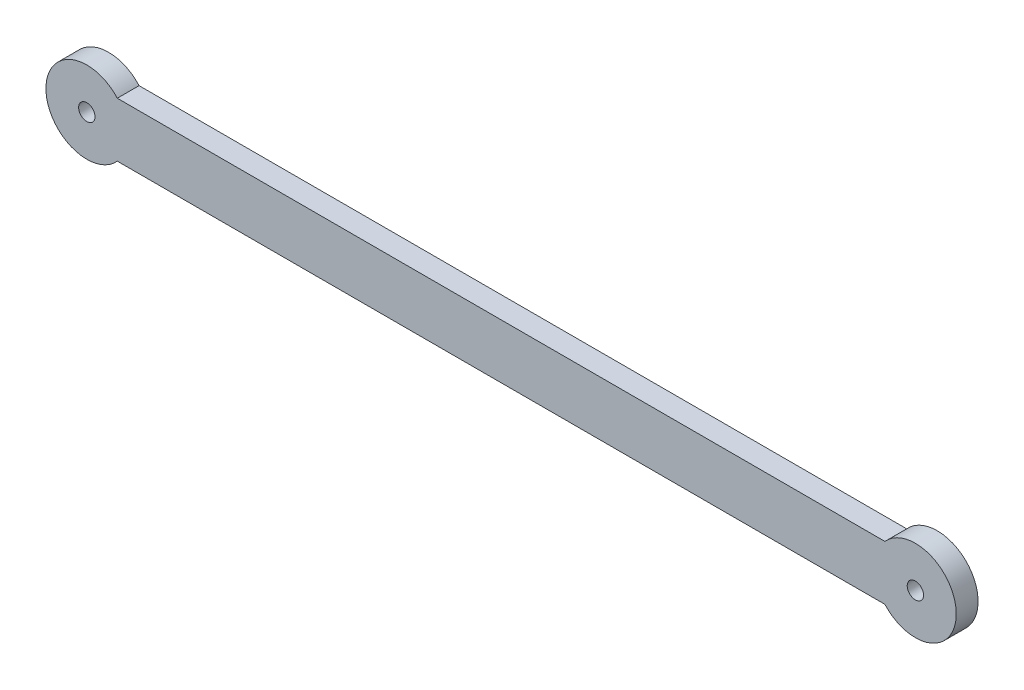
SolidWorks part; units mm, degrees
material "Acrílico (Impacto medio-alto)"
ref_plane "Piano frontale" through (0, 0, 0) normal (0, 0, 1) x (1, 0, 0)
ref_plane "Piano superiore" through (0, 0, 0) normal (0, 1, 0) x (1, 0, 0)
ref_plane "Piano destro" through (0, 0, 0) normal (1, 0, 0) x (0, 0, -1)
sketch "Schizzo1" plane through (0, 0, 0) normal (0, 0, 1) x (1, 0, 0)
  line L0 (0, 0) -> (1.5, 0) construction
  line L1 (5.5902, -5) -> (146.4098, -5)
  line L2 (5.5902, 5) -> (146.4098, 5)
  line L3 (0, 5) -> (152, 5) construction
  line L4 (0, -5) -> (152, -5) construction
  line L5 (150.5, 0) -> (152, 0) construction
  line L6 (0, 0) -> (152, 0) construction
  circle A0 centre (0, 0) radius 1.5
  circle A1 centre (152, 0) radius 1.5
  arc A2 (5.5902, 5) -> (5.5902, -5) centre (0, 0) ccw
  arc A3 (146.4098, -5) -> (146.4098, 5) centre (152, 0) ccw
  dimension "D1" = 3
  dimension "D2" = 3
  dimension "D4" = 15
  dimension "D5" = 15
  dimension "D3" = 152
  dimension "D6" = 5
  dimension "D7" = 5
extrude "Estrusione-Estrusione1" add sketch "Schizzo1" along normal blind 4
